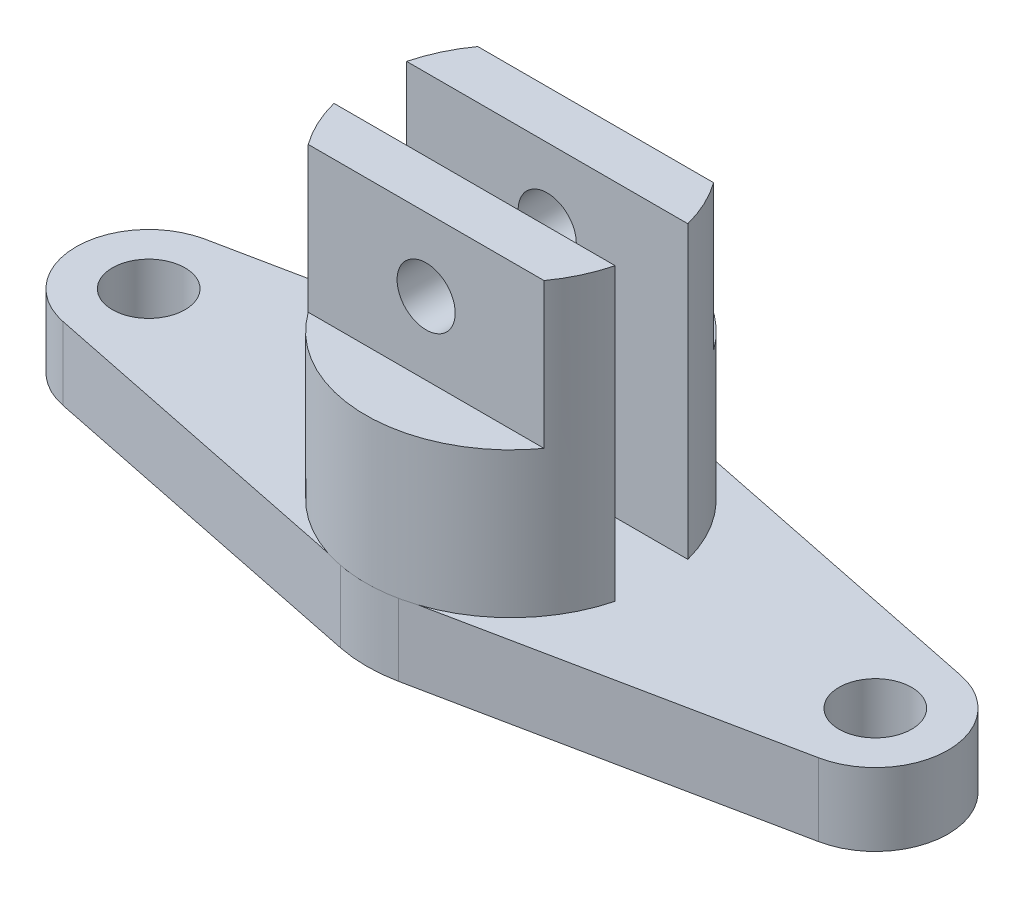
SolidWorks part; units mm, degrees
ref_plane "Front Plane" through (0, 0, 0) normal (0, 0, 1) x (1, 0, 0)
ref_plane "Top Plane" through (0, 0, 0) normal (0, 1, 0) x (1, 0, 0)
ref_plane "Right Plane" through (0, 0, 0) normal (1, 0, 0) x (0, 0, -1)
sketch "Sketch1" plane through (0, 0, 0) normal (0, 1, 0) x (1, 0, 0)
  line L6 (-78, 14.9223) -> (-6, 29.6192)
  line L7 (-78, -14.4716) -> (-6, -29.1685)
  line L8 (78, -14.4716) -> (6, -29.1685)
  line L9 (78, 14.9223) -> (6, 29.6192)
  arc A0 (-78, 14.9223) -> (-78, -14.4716) centre (-75, 0.2254) ccw
  arc A1 (6, 29.6192) -> (-6, 29.6192) centre (0, 0.2254) ccw
  arc A2 (78, 14.9223) -> (78, -14.4716) centre (75, 0.2254) cw
  arc A3 (-6, -29.1685) -> (6, -29.1685) centre (0, 0.2254) ccw
  point P0 (0, 0)
  dimension "D4" = 30
  dimension "D1" = 30
  dimension "D2" = 6
  dimension "D3" = 0.2254
extrude "Boss-Extrude1" add sketch "Sketch1" along normal blind 15
sketch "Sketch2" plane through (0, 15, 0) normal (0, 1, 0) x (1, 0, 0)
  line L0 (-29.0233, 7.5) -> (29.0233, 7.5)
  line L1 (-29.0233, -7.5) -> (29.0233, -7.5)
  arc A0 (-29.0233, -7.5) -> (29.0233, -7.5) centre (0, 0) ccw
  arc A1 (29.0233, 7.5) -> (-29.0233, 7.5) centre (0, 0) ccw
  dimension "D2" = 29.9767
  dimension "D1" = 15
extrude "Boss-Extrude2" add sketch "Sketch2" along normal blind 60
sketch "Sketch3" plane through (0, 75, 0) normal (0, 1, 0) x (1, 0, 0)
  line L0 (-24.367, 17.5) -> (24.367, 17.5)
  line L2 (-24.367, -17.5) -> (24.367, -17.5)
  arc A0 (24.367, 17.5) -> (-24.367, 17.5) centre (0, 0) ccw
  arc A2 (-24.367, -17.5) -> (24.367, -17.5) centre (0, 0) ccw
  dimension "D4" = 60
  dimension "D1" = 17.5
  dimension "D2" = 4.6563
  dimension "D5" = 58.0466
extrude "Cut-Extrude1" cut sketch "Sketch3" against normal blind 30
sketch "Sketch4" plane through (0, 0, 17.5) normal (0, 0, 1) x (1, 0, 0)
  line L1 (-90, 15) -> (-90, 0) construction
  line L2 (-78, 0) -> (-6, 0) construction
  circle A0 centre (0, 60) radius 6
  dimension "D2" = 12
  dimension "D1" = 90
  dimension "D3" = 60
extrude "Cut-Extrude2" cut sketch "Sketch4" against normal blind 64
sketch "Sketch5" plane through (0, 15, 0) normal (0, 1, 0) x (1, 0, 0)
  circle A0 centre (-75, 0.2254) radius 7.5
  circle A1 centre (75, 0.2254) radius 7.5
  dimension "D1" = 15
  dimension "D2" = 15
extrude "Cut-Extrude3" cut sketch "Sketch5" against normal blind 64
